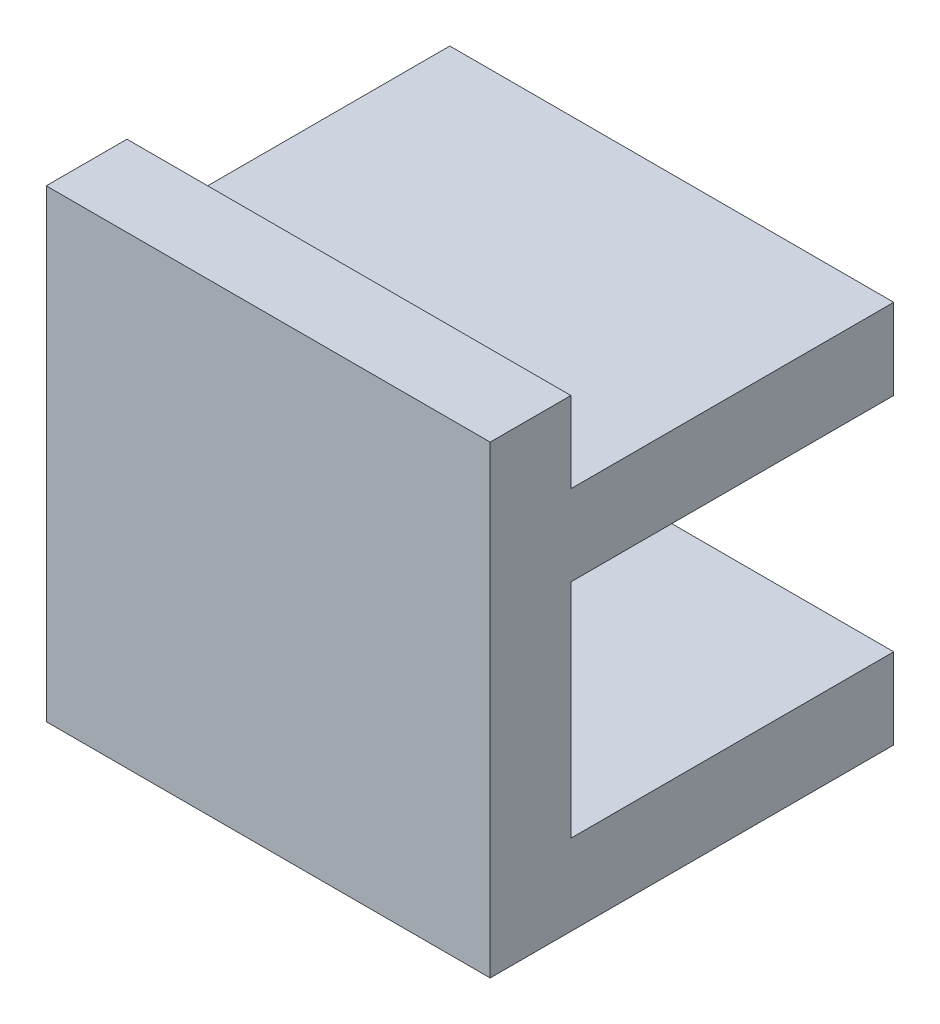
SolidWorks part; units mm, degrees
ref_plane "Спереди" through (0, 0, 0) normal (0, 0, 1) x (1, 0, 0)
ref_plane "Сверху" through (0, 0, 0) normal (0, 1, 0) x (1, 0, 0)
ref_plane "Справа" through (0, 0, 0) normal (1, 0, 0) x (0, 0, -1)
sketch "Эскиз1" plane through (0, 0, 0) normal (1, 0, 0) x (0, 0, -1)
  line L0 (10, -57.5) -> (90, -57.5)
  line L1 (-10, -57.5) -> (10, -57.5)
  line L2 (-10, -57.5) -> (-10, 57.5)
  line L3 (-10, 57.5) -> (10, 57.5)
  line L4 (10, -57.5) -> (10, 57.5)
  line L5 (-10, -57.5) -> (10, 57.5) construction
  line L6 (-10, 57.5) -> (10, -57.5) construction
  line L7 (90, -57.5) -> (90, -37.5)
  line L8 (90, -37.5) -> (10, -37.5)
  line L10 (10, 37.5) -> (90, 37.5)
  line L11 (10, 37.5) -> (10, 17.5)
  line L12 (10, 17.5) -> (90, 17.5)
  line L13 (90, 37.5) -> (90, 17.5)
  point P0 (0, 0)
  dimension "D1" = 20
  dimension "D2" = 115
  dimension "D3" = 20
  dimension "D4" = 80
  dimension "D6" = 20
extrude "Бобышка-Вытянуть1" add sketch "Эскиз1" along normal mid plane 110 contours L1 L4 L3 L2 | L7 L8 L4 L0 | L13 L10 L4 L12
